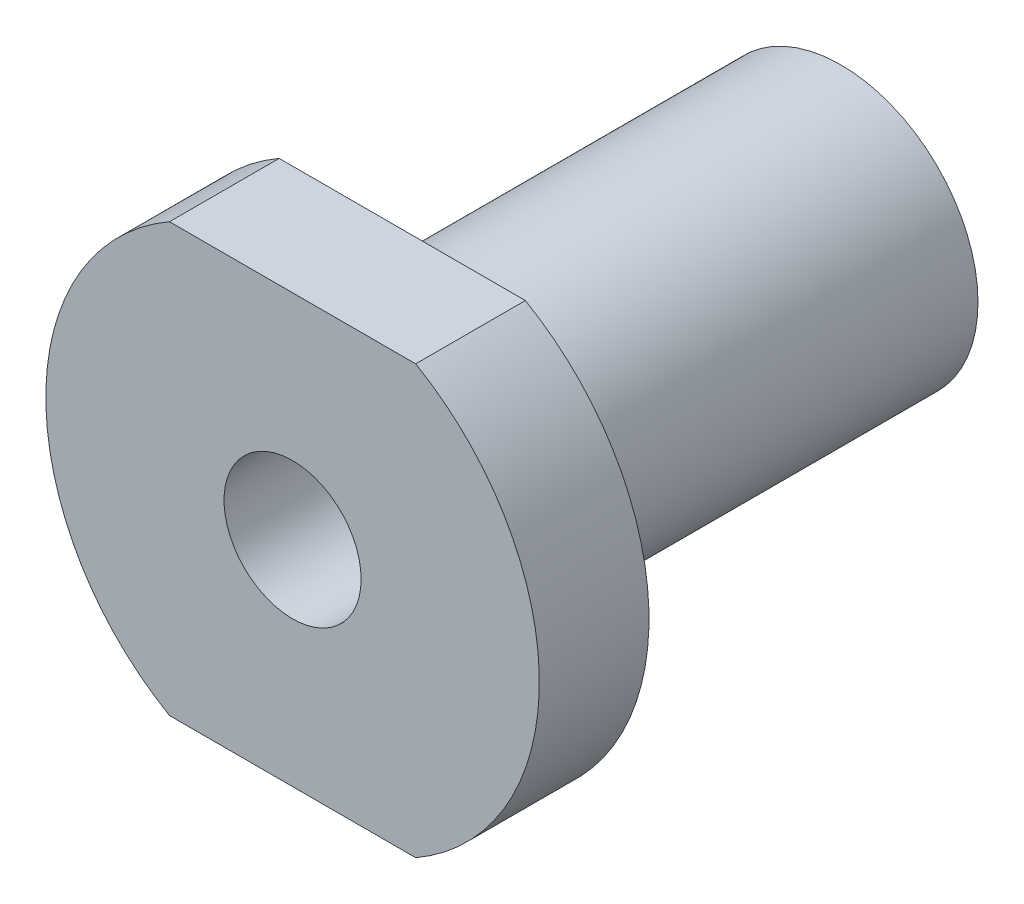
SolidWorks part; units mm, degrees
material "AISI 4340 Steel, annealed"
ref_plane "Front Plane" through (0, 0, 0) normal (0, 0, 1) x (1, 0, 0)
ref_plane "Top Plane" through (0, 0, 0) normal (0, 1, 0) x (1, 0, 0)
ref_plane "Right Plane" through (0, 0, 0) normal (1, 0, 0) x (0, 0, -1)
sketch "Sketch1" plane through (0, 0, 0) normal (0, 0, 1) x (1, 0, 0)
  circle A0 centre (0, 0) radius 4.5
  circle A1 centre (0, 0) radius 2.3
  dimension "D1" = 9
  dimension "D2" = 4.6
extrude "Boss-Extrude1" add sketch "Sketch1" along normal blind 2
sketch "Sketch2" plane through (0, 0, 2) normal (0, 0, 1) x (1, 0, 0)
  circle A0 centre (0, 0) radius 2.5
  circle A1 centre (0, 0) radius 1.25
  dimension "D1" = 2.5
  dimension "D2" = 5
extrude "Boss-Extrude2" add sketch "Sketch2" against normal blind 10
sketch "Sketch3" plane through (0, 0, 2) normal (0, 0, 1) x (1, 0, 0)
  line L1 (-5.5, -3.9) -> (5.5, -3.9)
  line L2 (-5.5, -3.9) -> (-5.5, 3.9)
  line L3 (-5.5, 3.9) -> (5.5, 3.9)
  line L4 (5.5, -3.9) -> (5.5, 3.9)
  line L5 (-5.5, -3.9) -> (5.5, 3.9) construction
  line L6 (-5.5, 3.9) -> (5.5, -3.9) construction
  circle A0 centre (0, 0) radius 9.5696
  point P0 (0, 0)
  dimension "D1" = 7.8
  dimension "D2" = 11
extrude "Cut-Extrude1" cut sketch "Sketch3" against normal blind 10
